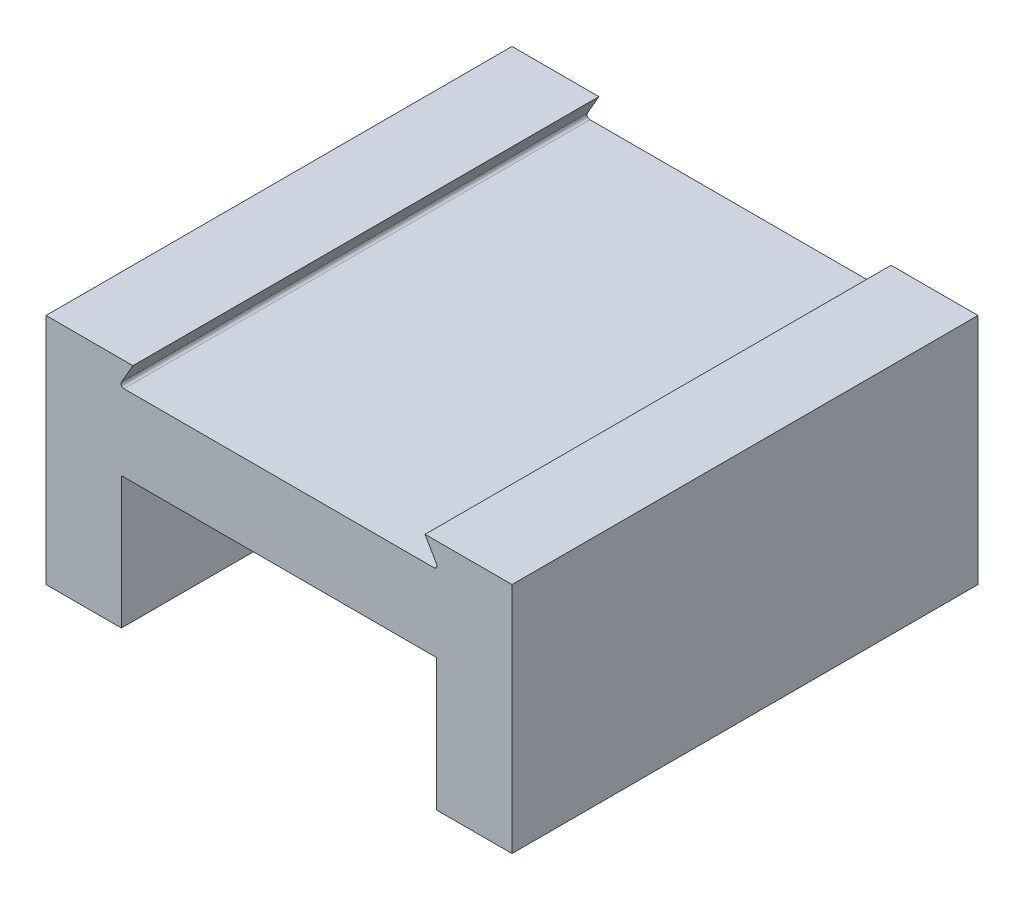
SolidWorks part; units mm, degrees
ref_plane "Front Plane" through (0, 0, 0) normal (0, 0, 1) x (1, 0, 0)
ref_plane "Top Plane" through (0, 0, 0) normal (0, 1, 0) x (1, 0, 0)
ref_plane "Right Plane" through (0, 0, 0) normal (1, 0, 0) x (0, 0, -1)
sketch "Sketch1" plane through (0, 0, 0) normal (0, 0, 1) x (1, 0, 0)
  line L0 (6.6953, 1.7004) -> (6.6953, 22.2441) construction
  line L2 (-23.3047, 17.7004) -> (-23.3047, -12.2996)
  line L4 (36.6953, 17.7004) -> (36.6953, -12.2996)
  line L5 (-12.111, 17.7004) -> (-13.5997, 15.1219)
  line L6 (-13.2698, 14.5504) -> (26.6604, 14.5504)
  line L7 (25.5017, 17.7004) -> (26.9904, 15.1219)
  line L9 (-23.3047, 17.7004) -> (-12.111, 17.7004)
  line L11 (25.5017, 17.7004) -> (36.6953, 17.7004)
  line L12 (-13.5997, 15.1219) -> (-13.5997, -8.3128) construction
  line L13 (26.9904, 15.1219) -> (26.9904, -9.2033) construction
  line L14 (-13.5997, -12.2996) -> (-13.5997, 4.7004)
  line L15 (-13.5997, 4.7004) -> (26.9904, 4.7004)
  line L17 (26.9904, -12.2996) -> (26.9904, 4.7004)
  line L18 (26.9904, -12.2996) -> (36.6953, -12.2996)
  line L20 (-23.3047, -12.2996) -> (-13.5997, -12.2996)
  arc A0 (-13.5997, 15.1219) -> (-13.2698, 14.5504) centre (-13.2698, 14.9314) ccw
  arc A1 (26.9904, 15.1219) -> (26.6604, 14.5504) centre (26.6604, 14.9314) cw
  point P11 (-13.9297, 14.5504)
  point P15 (6.6953, 14.5504)
  dimension "D5" = 0.381
  dimension "D1" = 60
  dimension "D2" = 60
  dimension "D3" = 3.15
  dimension "D4" = 20.625
  dimension "D6" = 30
  dimension "17" = 17
  dimension "D8" = 30
extrude "Boss-Extrude1" add sketch "Sketch1" along normal blind 60
sketch "Sketch2" plane through (-23.3047, 0, 0) normal (-1, 0, 0) x (0, 0, 1)
  line L0 (30, -12.2996) -> (30, 21.7768) construction
  line L1 (60, -12.2996) -> (0, -12.2996) construction
  circle A0 centre (15, -2.2996) radius 4.25
  circle A1 centre (45, -2.2996) radius 4.25
other "AlignGroup1" parameters "D1"=5.5134, "D2"=8.5, "D3"=9.149, "D4"=20, "D5"=40, "D6"=60
extrude "Cut-Extrude1" cut sketch "Sketch2" against normal up to surface (9.705 mm away) up to face at (-13.5997, -3.7996, 30)
